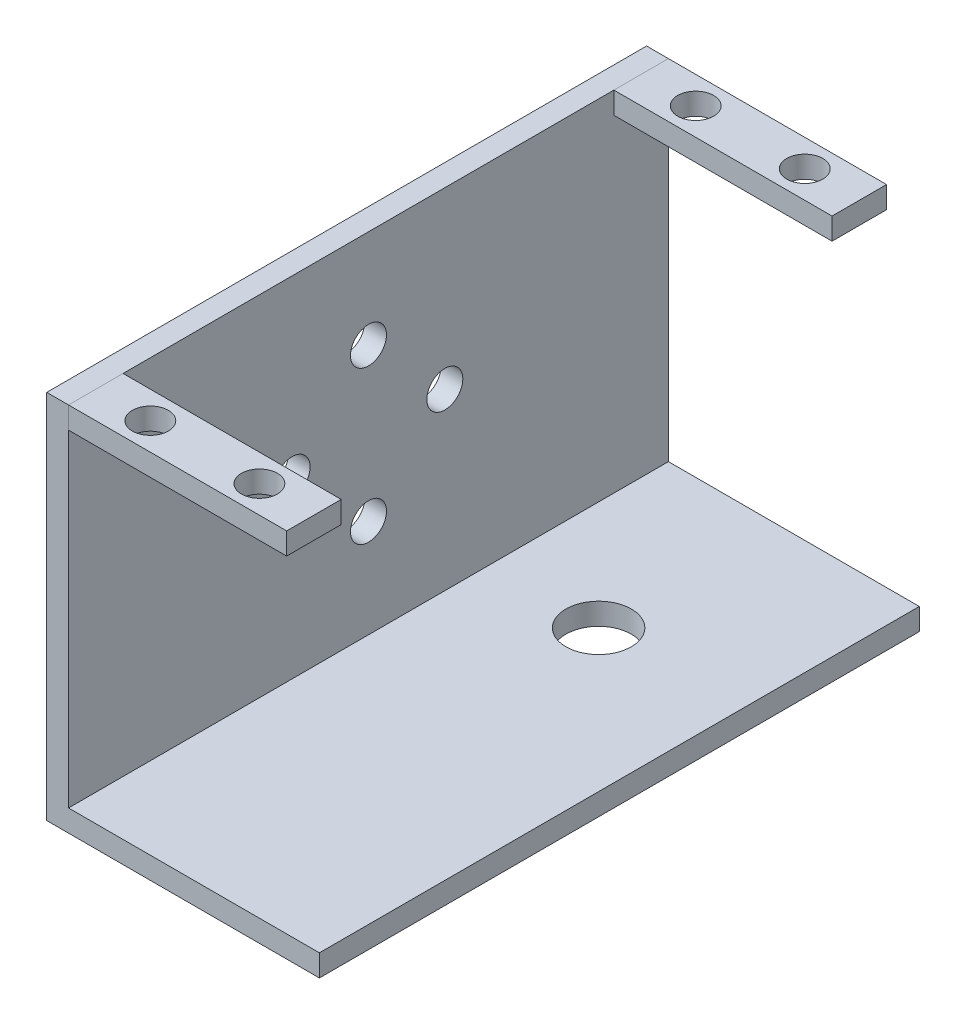
SolidWorks part; units mm, degrees
ref_plane "前视基准面" through (0, 0, 0) normal (0, 0, 1) x (1, 0, 0)
ref_plane "上视基准面" through (0, 0, 0) normal (0, 1, 0) x (1, 0, 0)
ref_plane "右视基准面" through (0, 0, 0) normal (1, 0, 0) x (0, 0, -1)
sketch "草图1" plane through (0, 0, 0) normal (0, 1, 0) x (1, 0, 0)
  line L1 (-12.5, -27.5) -> (12.5, -27.5)
  line L2 (-12.5, -27.5) -> (-12.5, 27.5)
  line L3 (-12.5, 27.5) -> (12.5, 27.5)
  line L4 (12.5, -27.5) -> (12.5, 27.5)
  line L5 (-12.5, -27.5) -> (12.5, 27.5) construction
  line L6 (-12.5, 27.5) -> (12.5, -27.5) construction
  point P1 (0, 0)
  dimension "D1" = 55
  dimension "D2" = 25
extrude "凸台-拉伸1" add sketch "草图1" along normal blind 2
sketch "草图3" plane through (0, 2, 0) normal (0, 1, 0) x (1, 0, 0)
  line L0 (-12.5, -27.5) -> (12.5, -27.5) construction
  line L1 (-12.5, 27.5) -> (-10.5, 27.5)
  line L2 (-12.5, 27.5) -> (-12.5, -27.5)
  line L3 (-12.5, -27.5) -> (-10.5, -27.5)
  line L4 (-10.5, 27.5) -> (-10.5, -27.5)
  dimension "D1" = 2
extrude "凸台-拉伸2" add sketch "草图3" along normal blind 32
sketch "草图4" plane through (-10.5, 0, 0) normal (1, 0, 0) x (0, 0, -1)
  line L0 (0, 34) -> (0, 2) construction
  line L1 (-27.5, 34) -> (27.5, 34) construction
  line L2 (-27.5, 2) -> (27.5, 2) construction
  line L3 (-22.5, 32) -> (22.5, 32) construction
  line L4 (22.5, 34) -> (27.5, 34)
  line L5 (-22.5, 32) -> (-27.5, 32)
  line L6 (-22.5, 32) -> (-22.5, 34)
  line L7 (-22.5, 34) -> (-27.5, 34)
  line L8 (-27.5, 32) -> (-27.5, 34)
  line L9 (27.5, 32) -> (27.5, 34)
  line L10 (22.5, 32) -> (27.5, 32)
  line L11 (22.5, 32) -> (22.5, 34)
  line L12 (-27.5, 2) -> (27.5, 2) construction
  dimension "D1" = 45
  dimension "D2" = 5
  dimension "D3" = 2
  dimension "D4" = 30
extrude "凸台-拉伸3" add sketch "草图4" along normal blind 20 separate body
sketch "草图5" plane through (0, 34, 0) normal (0, 1, 0) x (1, 0, 0)
  line L0 (-10.5, -25) -> (9.5, -25) construction
  line L1 (-10.5, -22.5) -> (-10.5, -27.5) construction
  line L2 (9.5, -22.5) -> (9.5, -27.5) construction
  line L3 (-12.5, 0) -> (-10.5, 0) construction
  line L4 (-12.5, 27.5) -> (-12.5, -27.5) construction
  line L5 (-10.5, -27.5) -> (-10.5, 27.5) construction
  circle A0 centre (-5.5, -25) radius 1.65
  circle A1 centre (4.5, -25) radius 1.65
  circle A2 centre (4.5, 25) radius 1.65
  circle A3 centre (-5.5, 25) radius 1.65
  dimension "D1" = 3.3
  dimension "D2" = 3.3
  dimension "D3" = 10
  dimension "D4" = 5
extrude "切除-拉伸2" cut sketch "草图5" against normal up to next (2 mm away)
sketch "草图6" plane through (-10.5, 0, 0) normal (1, 0, 0) x (0, 0, -1)
  line L0 (-27.5, 18) -> (27.5, 18) construction
  line L1 (-27.5, 34) -> (-27.5, 2) construction
  line L2 (27.5, 34) -> (27.5, 2) construction
  line L3 (0, 34) -> (0, 2) construction
  line L4 (-27.5, 34) -> (27.5, 34) construction
  line L5 (-27.5, 2) -> (27.5, 2) construction
  circle A0 centre (-7, 18) radius 1.65
  circle A1 centre (7, 18) radius 1.65
  circle A2 centre (0, 25) radius 1.65
  circle A3 centre (0, 11) radius 1.65
  dimension "D1" = 3.3
  dimension "D2" = 3.3
  dimension "D3" = 3.3
  dimension "D4" = 3.3
  dimension "D5" = 14
  dimension "D6" = 14
extrude "切除-拉伸3" cut sketch "草图6" against normal blind 10
sketch "草图7" plane through (0, 2, 0) normal (0, 1, 0) x (1, 0, 0)
  line L0 (4.5, 25) -> (-5.5, 25) construction
  line L1 (4.5, 25) -> (4.5, -25) construction
  circle A0 centre (-0.5, 11.1) radius 3
  dimension "D3" = 6
  dimension "D1" = 5
  dimension "D2" = 13.9
extrude "切除-拉伸4" cut sketch "草图7" against normal blind 10
